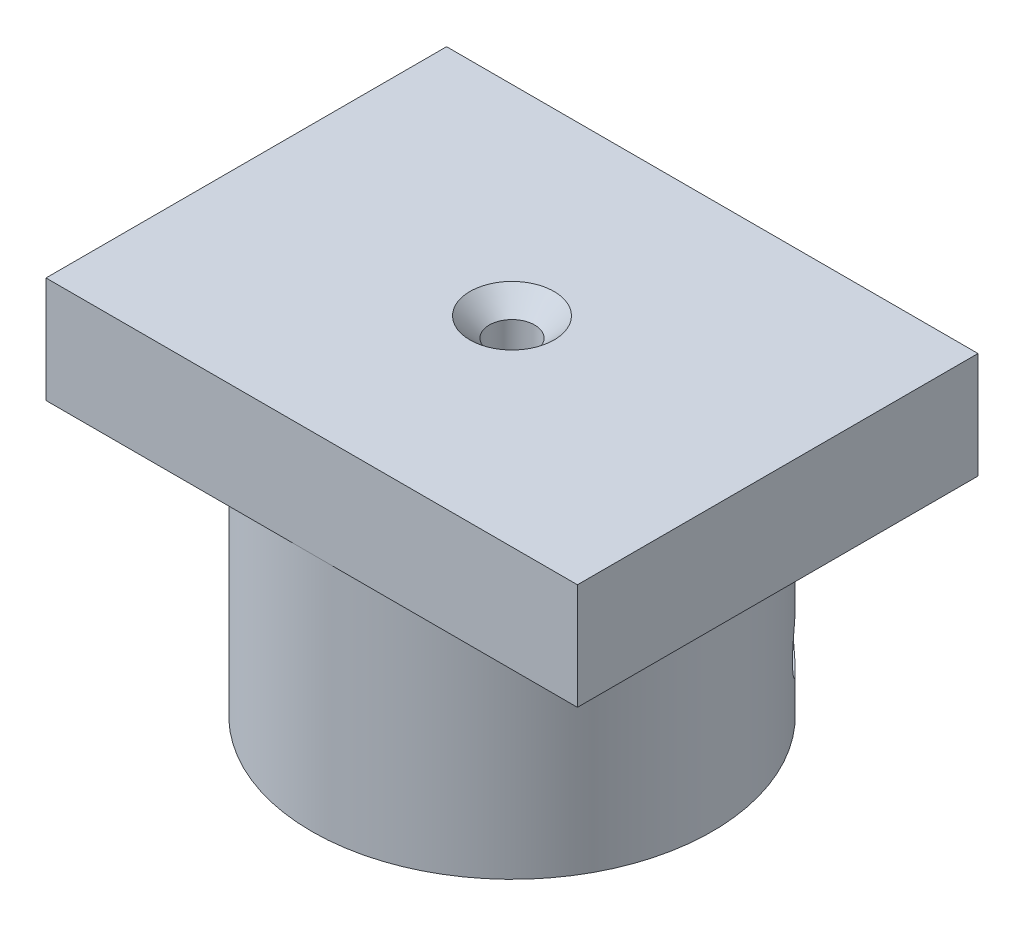
SolidWorks part; units mm, degrees
material "PET"
ref_plane "Front Plane" through (0, 0, 0) normal (0, 0, 1) x (1, 0, 0)
ref_plane "Top Plane" through (0, 0, 0) normal (0, 1, 0) x (1, 0, 0)
ref_plane "Right Plane" through (0, 0, 0) normal (1, 0, 0) x (0, 0, -1)
sketch "Sketch1" plane through (0, 0, 0) normal (0, 1, 0) x (1, 0, 0)
  circle A0 centre (0, 0) radius 4.5
  circle A1 centre (0, 0) radius 15
  dimension "D1" = 9
  dimension "D2" = 30
extrude "Boss-Extrude1" add sketch "Sketch1" along normal mid plane 18
sketch "Sketch2" plane through (0, 9, 0) normal (0, 1, 0) x (1, 0, 0)
  line L1 (19.9, -15) -> (-19.9, -15)
  line L2 (19.9, -15) -> (19.9, 15)
  line L3 (19.9, 15) -> (-19.9, 15)
  line L4 (-19.9, -15) -> (-19.9, 15)
  line L5 (19.9, -15) -> (-19.9, 15) construction
  line L6 (19.9, 15) -> (-19.9, -15) construction
  circle A0 centre (0, 0) radius 1.5
  point P0 (0, 0)
  dimension "D3" = 3
  dimension "D1" = 30
  dimension "D2" = 39.8
extrude "Boss-Extrude2" add sketch "Sketch2" along normal blind 7.95
sketch "Sketch3" plane through (0, 0, -15) normal (0, 0, -1) x (-1, 0, 0)
  line L0 (-19.9, 16.95) -> (19.9, 16.95) construction
  line L2 (19.9, 16.95) -> (19.9, 9) construction
  circle A0 centre (-0.1, 12.95) radius 1 construction
  dimension "D3" = 2
  dimension "D1" = 4
  dimension "D2" = 20
ref_plane "Plane1" through (0, 0, 0) normal (0.7071, 0, -0.7071) x (-0.7071, 0, -0.7071)
ref_plane "Plane2" through (0, 0, 0) normal (0.7071, 0, 0.7071) x (0.7071, 0, -0.7071)
hole_wizard "CSK for M3 Countersunk Flat Head Screw1" positions "Sketch10" profile "Sketch11" countersink size "M3" standard "DIN" end condition through all
sketch "Sketch10" plane through (0, 16.95, 0) normal (0, 1, 0) x (1, 0, 0)
  point P0 (0, 0)
sketch "Sketch11" plane through (0, 16.95, 0) normal (1, 0, 0) x (0, 0, 1)
  line L0 (0, 0) -> (0, 25.95)
  line L1 (0, 25.95) -> (1.7, 25.95)
  line L2 (1.7, 25.95) -> (1.7, 1.45)
  line L3 (1.7, 1.45) -> (3.15, 0)
  line L5 (3.15, 0) -> (0, 0)
  line L6 (-1.7, 1.45) -> (-3.15, 0) construction
  line L11 (0, -6.35) -> (0, 107.95) construction
  dimension "Thru Hole Dia." = 3.4
  dimension "Thru Hole Depth" = 25.95
  dimension "Near C'Sink Dia." = 6.3
  dimension "Near C'Sink Angle" = 90
ref_plane "Plane4" through (10.6066, 0, -10.6066) normal (0.7071, 0, -0.7071) x (-0.7071, 0, -0.7071)
sketch "Sketch18" plane through (10.6066, 0, -10.6066) normal (0.7071, 0, -0.7071) x (-0.7071, 0, -0.7071)
  line L0 (0, -9) -> (0, 9) construction
  line L2 (-15, -9) -> (15, -9) construction
  line L5 (-15, 9) -> (10.6066, 9) construction
hole_wizard "M5 Tapped Hole1" positions "Sketch22" profile "Sketch24" tap size "M5" standard "DIN"
sketch "Sketch22" plane through (10.6066, 0, -10.6066) normal (0.7071, 0, -0.7071) x (-0.7071, 0, -0.7071)
  line L0 (0, -9) -> (0, 9) construction
  point P0 (0, -4)
  dimension "D1" = 13
sketch "Sketch24" plane through (10.6066, -4, -10.6066) normal (0, 1, 0) x (-0.7071, 0, -0.7071)
  line L0 (0, 0) -> (0, 10.5)
  line L1 (0, 10.5) -> (2.1, 10.5)
  line L2 (2.1, 10.5) -> (2.1, 0)
  line L5 (2.1, 0) -> (0, 0)
  line L11 (0, -6.35) -> (0, 107.95) construction
  dimension "Thru Tap Drill Dia." = 4.2
  dimension "Thru Tap Drill Depth" = 10.5
cosmetic thread "Hole Thread1" parameters "D2"=5
thread "Thread1" pitch 0.8 start angle 0, offset 0, length 12, pitch 0.8, diameter 4.2
ref_plane "Plane5" through (12.0915, -4, -9.1217) normal (0, -1, 0) x (0.7071, 0, 0.7071)
sketch "Thread Profile2" plane through (12.0915, -4, -9.1217) normal (0, -1, 0) x (0.7071, 0, 0.7071)
  line L0 (0, 0) -> (0, 0.8) construction
  line L1 (0, 0) -> (0.433, 0.25)
  line L2 (0.433, 0.25) -> (0.433, 0.35)
  line L3 (0.433, 0.35) -> (0, 0.6)
  line L4 (0.433, 0.3) -> (0, 0.3) construction
  line L11 (0, 0) -> (0, 0.6)
  point P2 (0, 0)
  dimension "Pitch" = 0.8
  dimension "Profile_Angle" = 60
  dimension "Profile_Land" = 0.1
  dimension "Profile_Height" = 0.433
ref_plane "Plane6" through (-10.6066, 0, -10.6066) normal (-0.7071, 0, -0.7071) x (-0.7071, 0, 0.7071)
sketch "Sketch29" plane through (-10.6066, 0, -10.6066) normal (-0.7071, 0, -0.7071) x (-0.7071, 0, 0.7071)
  line L0 (0, -9) -> (0, 9) construction
  line L1 (-15, -9) -> (15, -9) construction
  line L2 (-10.6066, 9) -> (15, 9) construction
hole_wizard "M5 Tapped Hole2" positions "Sketch31" profile "Sketch32" tap size "M5" standard "DIN"
sketch "Sketch31" plane through (-10.6066, 0, -10.6066) normal (-0.7071, 0, -0.7071) x (-0.7071, 0, 0.7071)
  line L0 (0, -9) -> (0, 9) construction
  point P0 (0, -4)
  dimension "D1" = 13
sketch "Sketch32" plane through (-10.6066, -4, -10.6066) normal (0, 1, 0) x (-0.7071, 0, 0.7071)
  line L0 (0, 0) -> (0, 10.5)
  line L1 (0, 10.5) -> (2.1, 10.5)
  line L2 (2.1, 10.5) -> (2.1, 0)
  line L5 (2.1, 0) -> (0, 0)
  line L11 (0, -6.35) -> (0, 107.95) construction
  dimension "Thru Tap Drill Dia." = 4.2
  dimension "Thru Tap Drill Depth" = 10.5
cosmetic thread "Hole Thread2" parameters "D2"=5
thread "Thread2" pitch 0.8 start angle 0, offset 0, length 12, pitch 0.8, diameter 4.2
ref_plane "Plane7" through (-9.1217, -4, -12.0915) normal (0, -1, 0) x (0.7071, 0, -0.7071)
sketch "Thread Profile3" plane through (-9.1217, -4, -12.0915) normal (0, -1, 0) x (0.7071, 0, -0.7071)
  line L0 (0, 0) -> (0, 0.8) construction
  line L1 (0, 0) -> (0.433, 0.25)
  line L2 (0.433, 0.25) -> (0.433, 0.35)
  line L3 (0.433, 0.35) -> (0, 0.6)
  line L4 (0.433, 0.3) -> (0, 0.3) construction
  line L11 (0, 0) -> (0, 0.6)
  point P2 (0, 0)
  dimension "Pitch" = 0.8
  dimension "Profile_Angle" = 60
  dimension "Profile_Land" = 0.1
  dimension "Profile_Height" = 0.433
sketch "Sketch33" plane through (0, 0, 0) normal (1, 0, 0) x (0, 0, -1)
  line L0 (0, 0) -> (0, 200) construction
  dimension "D1" = 200
sketch "Sketch34" plane through (0, 0, 15) normal (0, 0, 1) x (1, 0, 0)
  line L0 (-19.9, 12.75) -> (19.9, 12.75) construction
  line L1 (-19.9, 16.95) -> (-19.9, 9) construction
  line L2 (19.9, 16.95) -> (19.9, 9) construction
  line L3 (0, 9) -> (19.9, 9) construction
  circle A0 centre (0, 12.75) radius 1.5
  dimension "D2" = 3
  dimension "D1" = 3.75
